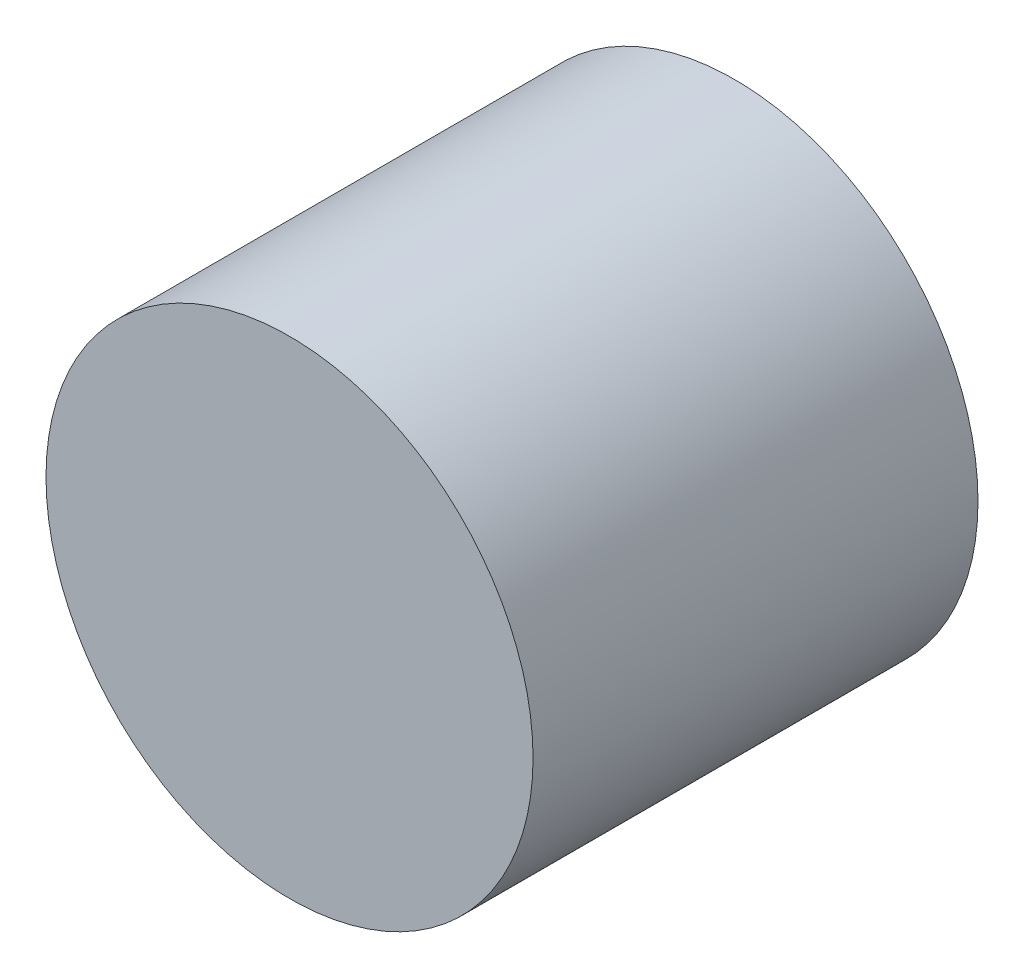
SolidWorks part; units mm, degrees
ref_plane "Front" through (0, 0, 0) normal (0, 0, 1) x (1, 0, 0)
ref_plane "Top" through (0, 0, 0) normal (0, 1, 0) x (1, 0, 0)
ref_plane "Right" through (0, 0, 0) normal (1, 0, 0) x (0, 0, -1)
sketch "Sketch1" plane through (0, 0, 0) normal (0, 0, 1) x (1, 0, 0)
  circle A0 centre (0, 0) radius 27.8042
extrude "Extrude1" add sketch "Sketch1" along normal blind 50.8
